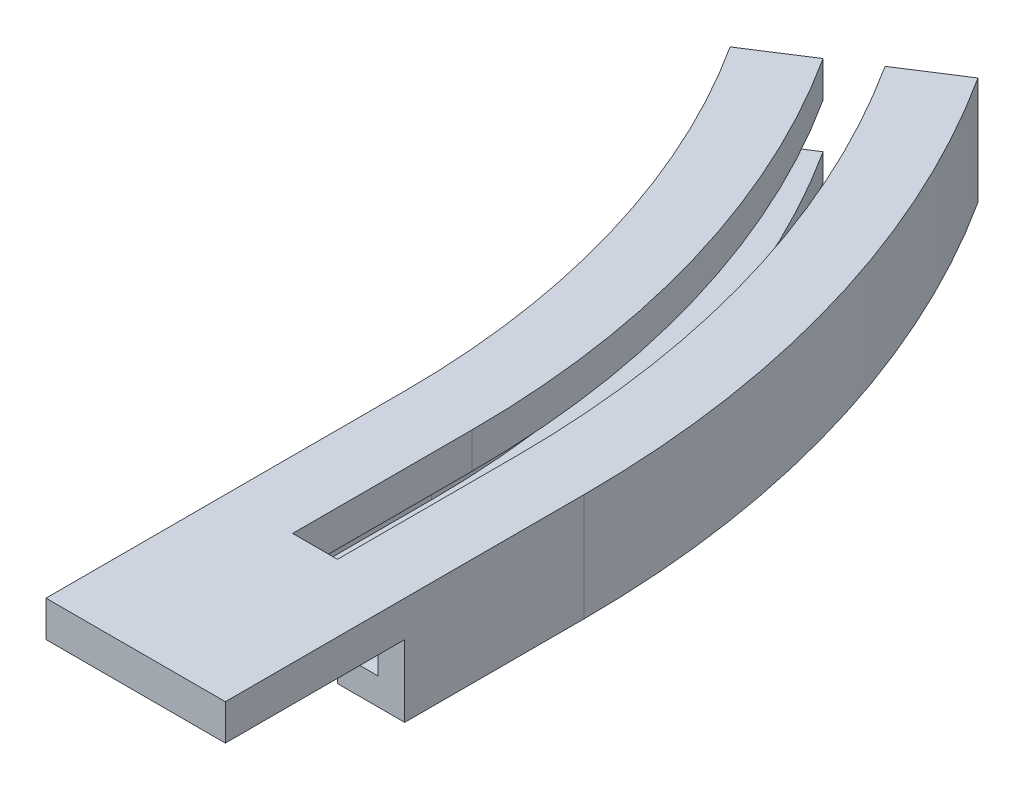
SolidWorks part; units mm, degrees
ref_plane "Front Plane" through (0, 0, 0) normal (0, 0, 1) x (1, 0, 0)
ref_plane "Top Plane" through (0, 0, 0) normal (0, 1, 0) x (1, 0, 0)
ref_plane "Right Plane" through (0, 0, 0) normal (1, 0, 0) x (0, 0, -1)
sketch "Sketch1" plane through (0, 0, 0) normal (0, 1, 0) x (1, 0, 0)
  line L0 (0, 0) -> (87.5, 0)
  line L1 (0, 0) -> (102.5, 0) construction
  line L2 (0, 0) -> (79.9077, 51.3786) construction
  line L3 (0, 0) -> (73.5992, 47.3224) construction
  line L4 (0, 0) -> (95, 0)
  line L5 (0, 0) -> (79.9077, 51.3786) construction
  line L6 (0, 0) -> (102.5, 0)
  line L7 (0, 0) -> (79.9077, 51.3786)
  line L8 (0, 0) -> (79.9077, 51.3786)
  line L9 (96.7303, 62.1952) -> (103.0388, 66.2514) construction
  line L10 (79.9077, 51.3786) -> (96.7303, 62.1952)
  line L11 (77.674, 54.6969) -> (94.5088, 65.5216)
  line L12 (95, 0) -> (95, -40)
  line L13 (95, -40) -> (115, -40)
  line L14 (115, -40) -> (115, 0)
  line L15 (95, 0) -> (102.5, 0)
  line L16 (107.5, 0) -> (122.5, 0) construction
  line L17 (107.5, 0) -> (115, 0)
  line L18 (107.5, 0) -> (115, 0)
  line L19 (102.5, 0) -> (102.5, -20)
  line L20 (107.5, 0) -> (107.5, -20)
  line L21 (107.5, -20) -> (102.5, -20)
  arc A0 (122.5, 0) -> (103.0388, 66.2514) centre (0, 0) ccw construction
  arc A1 (87.5, 0) -> (73.5992, 47.3224) centre (0, 0) ccw construction
  arc A2 (95, 0) -> (79.9077, 51.3786) centre (0, 0) ccw
  arc A3 (115, 0) -> (96.7303, 62.1952) centre (0, 0) ccw
  arc A4 (102.5, 0) -> (86.2162, 55.4348) centre (0, 0) ccw
  arc A5 (107.5, 0) -> (90.4218, 58.139) centre (0, 0) ccw
  arc A6 (95, 0) -> (77.674, 54.6969) centre (0, 0) ccw
  arc A7 (115, 0) -> (94.5088, 65.5216) centre (0, 0) ccw
  arc A8 (115, 0) -> (94.0264, 66.212) centre (0, 0) ccw construction
  dimension "D7" = 4
  dimension "D1" = 87.5
  dimension "D2" = 122.5
  dimension "D3" = 122.5
  dimension "D4" = 32.74
  dimension "D5" = 87.5
  dimension "D6" = 95
  dimension "D8" = 115
  dimension "D9" = 95
  dimension "D10" = 115
  dimension "D13" = 20
  dimension "D14" = 4
  dimension "D15" = 40
  dimension "D16" = 20
  dimension "D11" = 7.5
  dimension "D12" = 7.5
extrude "Boss-Extrude1" add sketch "Sketch1" along normal blind 4 contours L6 A4 L10 A2 | A5 L17 A3 L10 | L20 L21 L19 L6 L12 L13 L14 L17
sketch "Sketch2" plane through (0, 0, 0) normal (0, -1, 0) x (1, 0, 0)
  line L2 (98, 0) -> (98, 20)
  line L5 (112, 0) -> (112, 20)
  line L6 (95, 0) -> (95, 40) construction
  line L7 (95, 0) -> (95, 40)
  line L8 (115, 40) -> (115, 0) construction
  line L9 (115, 40) -> (115, 0)
  line L10 (115, 20) -> (112, 20)
  line L11 (79.9077, -51.3786) -> (82.4311, -53.0011)
  line L12 (94.2069, -60.5727) -> (96.7303, -62.1952)
  line L13 (98, 20) -> (95, 20)
  arc A2 (82.4311, -53.0011) -> (98, 0) centre (0, 0) ccw
  arc A5 (94.2069, -60.5727) -> (112, 0) centre (0, 0) ccw
  arc A6 (79.9077, -51.3786) -> (95, 0) centre (0, 0) ccw construction
  arc A7 (79.9077, -51.3786) -> (95, 0) centre (0, 0) ccw
  arc A8 (96.7303, -62.1952) -> (115, 0) centre (0, 0) ccw construction
  arc A9 (96.7303, -62.1952) -> (115, 0) centre (0, 0) ccw
  arc M3 (95, 0) -> (79.9077, -51.3786) centre (0, 0) cw
  line M4 (79.9077, -51.3786) -> (86.2162, -55.4348)
  line M10 (90.4218, -58.139) -> (96.7303, -62.1952)
  arc M11 (96.7303, -62.1952) -> (115, 0) centre (0, 0) ccw
  line M12 (115, 0) -> (115, 40)
extrude "Boss-Extrude2" add sketch "Sketch2" along normal blind 5 contours A5 L10 L5 M10 M11 M12 | A2 L2 L13 L7 M4 M3
sketch "Sketch3" plane through (0, -5, 0) normal (0, -1, 0) x (1, 0, 0)
  line L0 (98, 20) -> (112, 20)
  line L1 (82.4311, -53.0011) -> (94.2069, -60.5727)
  line L4 (79.9077, -51.3786) -> (82.4311, -53.0011)
  line L5 (98, 0) -> (98, 20)
  line L6 (98, 20) -> (95, 20)
  line L7 (95, 20) -> (95, 0)
  line L8 (79.9077, -51.3786) -> (82.4311, -53.0011)
  line L10 (98, 20) -> (95, 20)
  line L11 (95, 20) -> (95, 0)
  line L12 (94.2069, -60.5727) -> (96.7303, -62.1952)
  line L13 (115, 0) -> (115, 20)
  line L14 (115, 20) -> (112, 20)
  line L15 (112, 20) -> (112, 0)
  line L16 (94.2069, -60.5727) -> (96.7303, -62.1952)
  line L17 (115, 0) -> (115, 20)
  line L18 (115, 20) -> (112, 20)
  arc A2 (82.4311, -53.0011) -> (98, 0) centre (0, 0) ccw
  arc A3 (79.9077, -51.3786) -> (95, 0) centre (0, 0) ccw
  arc A5 (79.9077, -51.3786) -> (95, 0) centre (0, 0) ccw
  arc A6 (94.2069, -60.5727) -> (112, 0) centre (0, 0) ccw
  arc A7 (96.7303, -62.1952) -> (115, 0) centre (0, 0) ccw
  arc A9 (96.7303, -62.1952) -> (115, 0) centre (0, 0) ccw
  dimension "D1" = 0
  dimension "D2" = 0
extrude "Boss-Extrude3" add sketch "Sketch3" along normal blind 3
sketch "Sketch4" plane through (0, 4, 0) normal (0, 1, 0) x (1, 0, 0)
  line L0 (90.4218, 58.139) -> (86.2162, 55.4348)
  line L8 (95, 0) -> (95, -40)
  line L9 (95, -40) -> (115, -40)
  line L10 (115, -40) -> (115, 0)
  line L11 (96.7303, 62.1952) -> (90.4218, 58.139)
  line L12 (107.5, 0) -> (107.5, -20)
  line L13 (107.5, -20) -> (102.5, -20)
  line L14 (102.5, -20) -> (102.5, 0)
  line L15 (86.2162, 55.4348) -> (79.9077, 51.3786)
  line L20 (107.5, 0) -> (107.5, -20)
  line L21 (107.5, -20) -> (102.5, -20)
  line L22 (102.5, -20) -> (102.5, 0)
  arc A4 (95, 0) -> (79.9077, 51.3786) centre (0, 0) ccw
  arc A5 (115, 0) -> (96.7303, 62.1952) centre (0, 0) ccw
  arc A6 (107.5, 0) -> (90.4218, 58.139) centre (0, 0) ccw
  arc A7 (102.5, 0) -> (86.2162, 55.4348) centre (0, 0) ccw
  arc A10 (107.5, 0) -> (90.4218, 58.139) centre (0, 0) ccw
  arc A11 (102.5, 0) -> (86.2162, 55.4348) centre (0, 0) ccw
  dimension "D1" = 0
extrude "Cut-Extrude1" cut sketch "Sketch4" against normal blind 43
